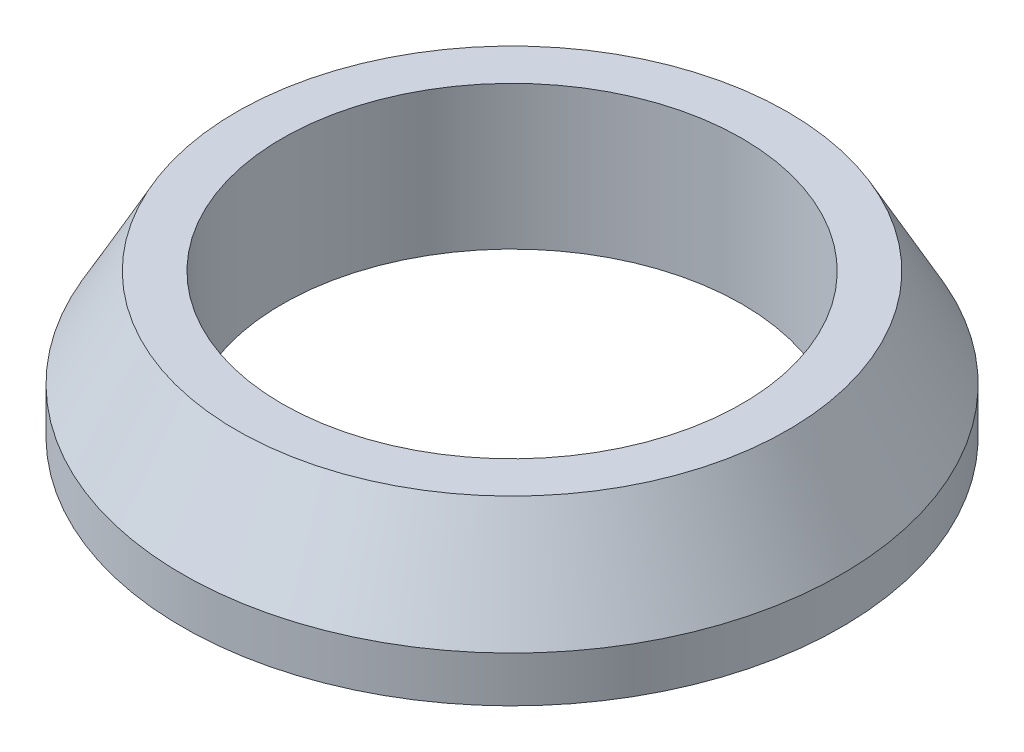
SolidWorks part; units mm, degrees
material "ABS PC"
ref_plane "Front Plane" through (0, 0, 0) normal (0, 0, 1) x (1, 0, 0)
ref_plane "Top Plane" through (0, 0, 0) normal (0, 1, 0) x (1, 0, 0)
ref_plane "Right Plane" through (0, 0, 0) normal (1, 0, 0) x (0, 0, -1)
sketch "Sketch1" plane through (0, 0, 0) normal (0, 0, 1) x (1, 0, 0)
  line L0 (6.3881, 0) -> (9.1567, 0)
  line L1 (1.5227, 0) -> (-1.5227, 0) construction
  line L2 (9.1567, 0) -> (9.1567, 1.27)
  line L3 (9.1567, 1.27) -> (7.6581, 3.9878)
  line L4 (7.6581, 3.9878) -> (6.3881, 3.9878)
  line L5 (6.3881, 3.9878) -> (6.3881, 0)
  line L6 (0, 0) -> (0, 2.3189) construction
  dimension "D1" = 6.3881
  dimension "D2" = 9.1567
  dimension "D3" = 3.9878
  dimension "D4" = 1.27
  dimension "D5" = 1.27
revolve "Revolve1" add sketch "Sketch1" angle 360 about L6
